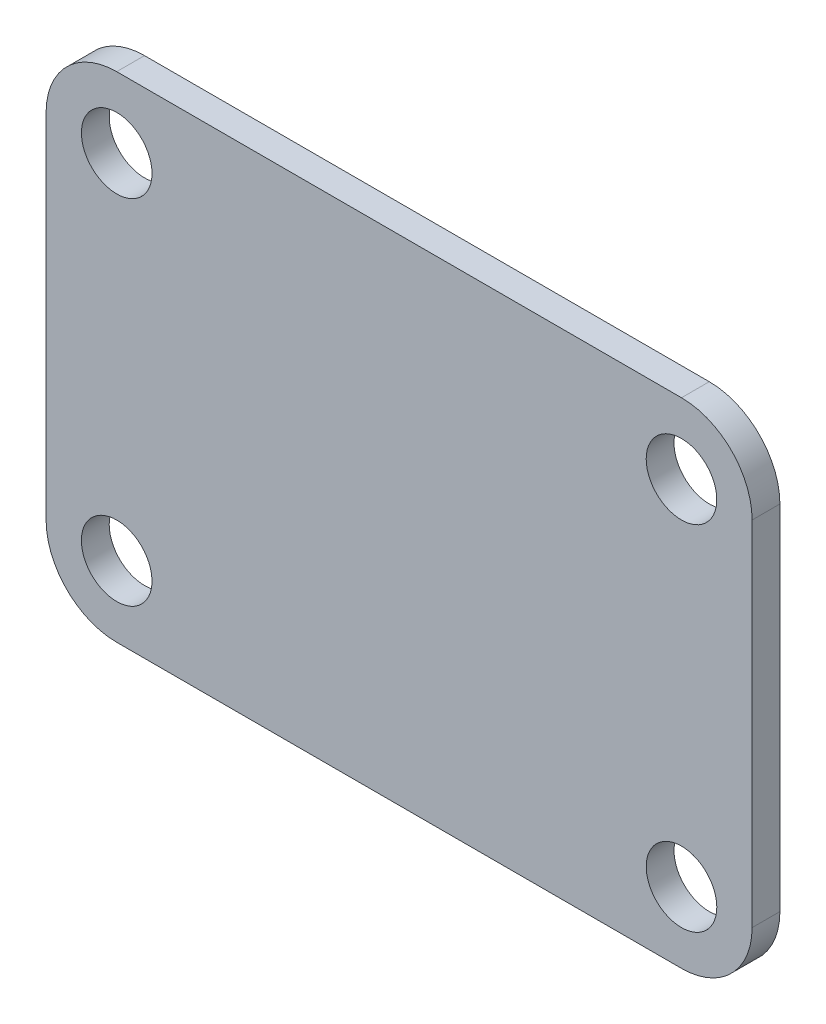
SolidWorks part; units mm, degrees
ref_plane "Alzado" through (0, 0, 0) normal (0, 0, 1) x (1, 0, 0)
ref_plane "Planta" through (0, 0, 0) normal (0, 1, 0) x (1, 0, 0)
ref_plane "Vista lateral" through (0, 0, 0) normal (1, 0, 0) x (0, 0, -1)
sketch "Croquis1" plane through (0, 0, 0) normal (0, 0, 1) x (1, 0, 0)
  line L0 (0, 8.89) -> (0, -8.89) construction
  line L1 (10.16, -8.89) -> (-10.16, -8.89)
  line L2 (12.7, -6.35) -> (12.7, 6.35)
  line L3 (10.16, 8.89) -> (-10.16, 8.89)
  line L4 (-12.7, -6.35) -> (-12.7, 6.35)
  line L5 (12.7, -8.89) -> (-12.7, 8.89) construction
  line L6 (12.7, 8.89) -> (-12.7, -8.89) construction
  line L7 (-12.7, 0) -> (12.7, 0) construction
  circle A0 centre (-10.16, 6.35) radius 1.27
  circle A1 centre (10.16, 6.35) radius 1.27
  circle A2 centre (10.16, -6.35) radius 1.27
  circle A3 centre (-10.16, -6.35) radius 1.27
  arc A4 (10.16, -8.89) -> (12.7, -6.35) centre (10.16, -6.35) ccw
  arc A5 (12.7, 6.35) -> (10.16, 8.89) centre (10.16, 6.35) ccw
  arc A6 (-10.16, -8.89) -> (-12.7, -6.35) centre (-10.16, -6.35) cw
  arc A7 (-10.16, 8.89) -> (-12.7, 6.35) centre (-10.16, 6.35) ccw
  point P0 (0, 0)
  dimension "D3" = 2.54
  dimension "D4" = 10.16
  dimension "D5" = 6.35
  dimension "D6" = 2.54
  dimension "D1" = 25.4
  dimension "D2" = 17.78
extrude "Saliente-Extruir1" add sketch "Croquis1" along normal blind 1
